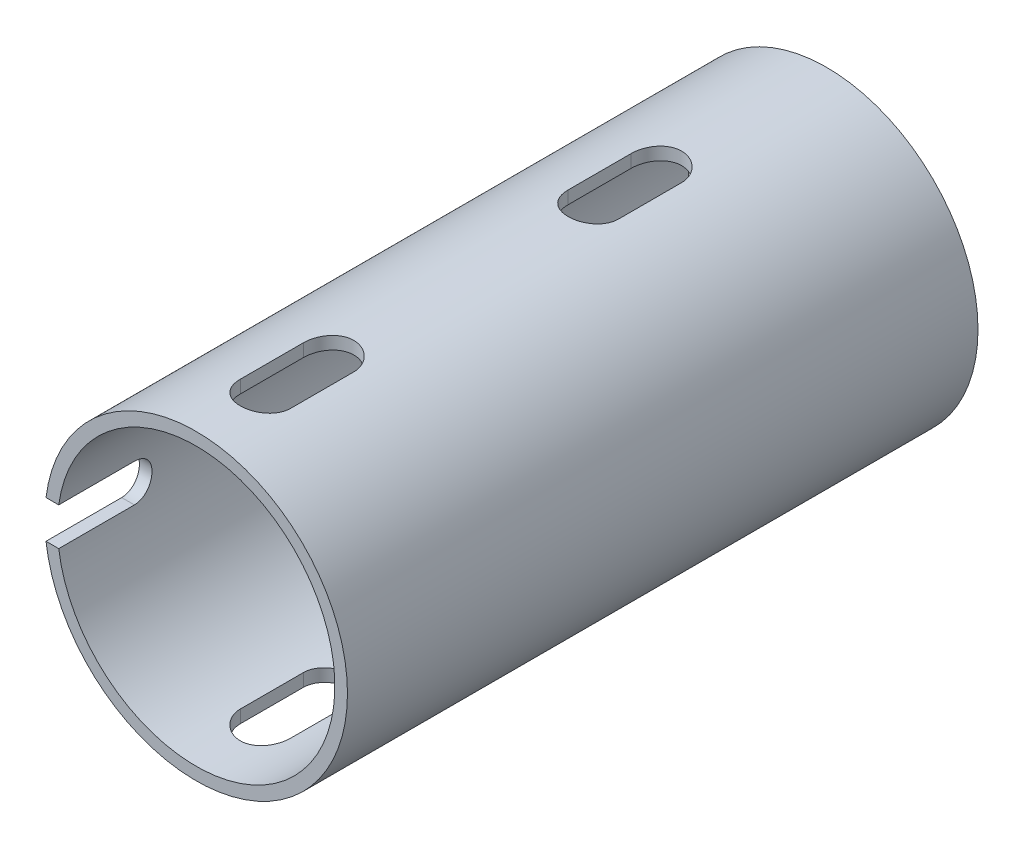
SolidWorks part; units mm, degrees
material "1060-H16"
ref_plane "前视基准面" through (0, 0, 0) normal (0, 0, 1) x (1, 0, 0)
ref_plane "上视基准面" through (0, 0, 0) normal (0, 1, 0) x (1, 0, 0)
ref_plane "右视基准面" through (0, 0, 0) normal (1, 0, 0) x (0, 0, -1)
sketch "草图1" plane through (0, 0, 0) normal (0, 0, 1) x (1, 0, 0)
  circle A0 centre (0, 0) radius 22
  circle A1 centre (0, 0) radius 24
  dimension "D1" = 48
  dimension "D2" = 44
extrude "凸台-拉伸1" add sketch "草图1" along normal mid plane 100
ref_plane "基准面1" through (-24, 0, 0) normal (-1, 0, 0) x (0, 0, 1)
sketch "草图2" plane through (-24, 0, 0) normal (-1, 0, 0) x (0, 0, 1)
  line L0 (38, 3) -> (50, 3)
  line L1 (50, -24) -> (50, 24) construction
  line L2 (50, 3) -> (50, -3)
  line L3 (50, -3) -> (38, -3)
  arc A0 (38, 3) -> (38, -3) centre (38, 0) ccw
  point P1 (50, 0)
  dimension "D2" = 3
  dimension "D1" = 12
extrude "切除-拉伸1" cut sketch "草图2" against normal blind 20
ref_plane "基准面2" through (0, 24, 0) normal (0, 1, 0) x (1, 0, 0)
sketch "草图3" plane through (0, 24, 0) normal (0, 1, 0) x (1, 0, 0)
  line L0 (0, 13) -> (0, 23) construction
  line L1 (-4, 13) -> (-4, 23)
  line L2 (4, 13) -> (4, 23)
  line L3 (0, -39) -> (0, -29) construction
  line L4 (-4, -39) -> (-4, -29)
  line L5 (4, -39) -> (4, -29)
  line L6 (0, 9) -> (0, -25) construction
  arc A0 (-4, 13) -> (4, 13) centre (0, 13) ccw
  arc A1 (4, 23) -> (-4, 23) centre (0, 23) ccw
  arc A2 (-4, -39) -> (4, -39) centre (0, -39) ccw
  arc A3 (4, -29) -> (-4, -29) centre (0, -29) ccw
  point P3 (0, 18)
  point P8 (0, -34)
  point P16 (0, -8)
  dimension "D3" = 4
  dimension "D1" = 10
  dimension "D2" = 10
  dimension "D4" = 52
  dimension "D5" = 8
extrude "切除-拉伸2" cut sketch "草图3" against normal through all
